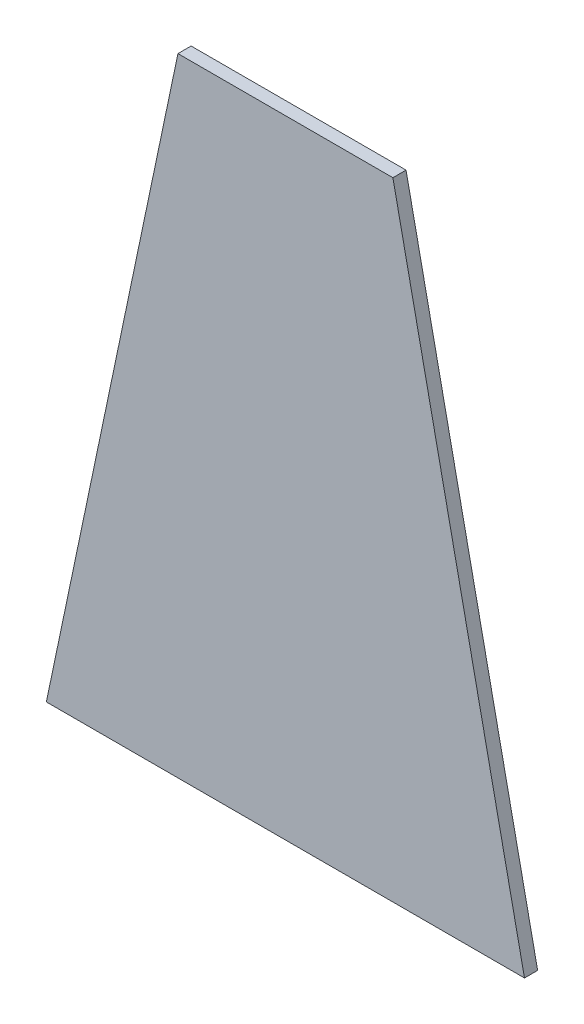
SolidWorks part; units mm, degrees
ref_plane "Front Plane" through (0, 0, 0) normal (0, 0, 1) x (1, 0, 0)
ref_plane "Top Plane" through (0, 0, 0) normal (0, 1, 0) x (1, 0, 0)
ref_plane "Right Plane" through (0, 0, 0) normal (1, 0, 0) x (0, 0, -1)
sketch "Sketch1" plane through (0, 0, 0) normal (0, 0, 1) x (1, 0, 0)
  line L0 (54.5, 143) -> (54.5, 0) construction
  line L1 (0, 0) -> (109, 0)
  line L2 (0, 0) -> (30, 143)
  line L3 (30, 143) -> (79, 143)
  line L4 (109, 0) -> (79, 143)
  dimension "D1" = 143
  dimension "D2" = 109
  dimension "D3" = 49
extrude "Boss-Extrude1" add sketch "Sketch1" along normal blind 3
